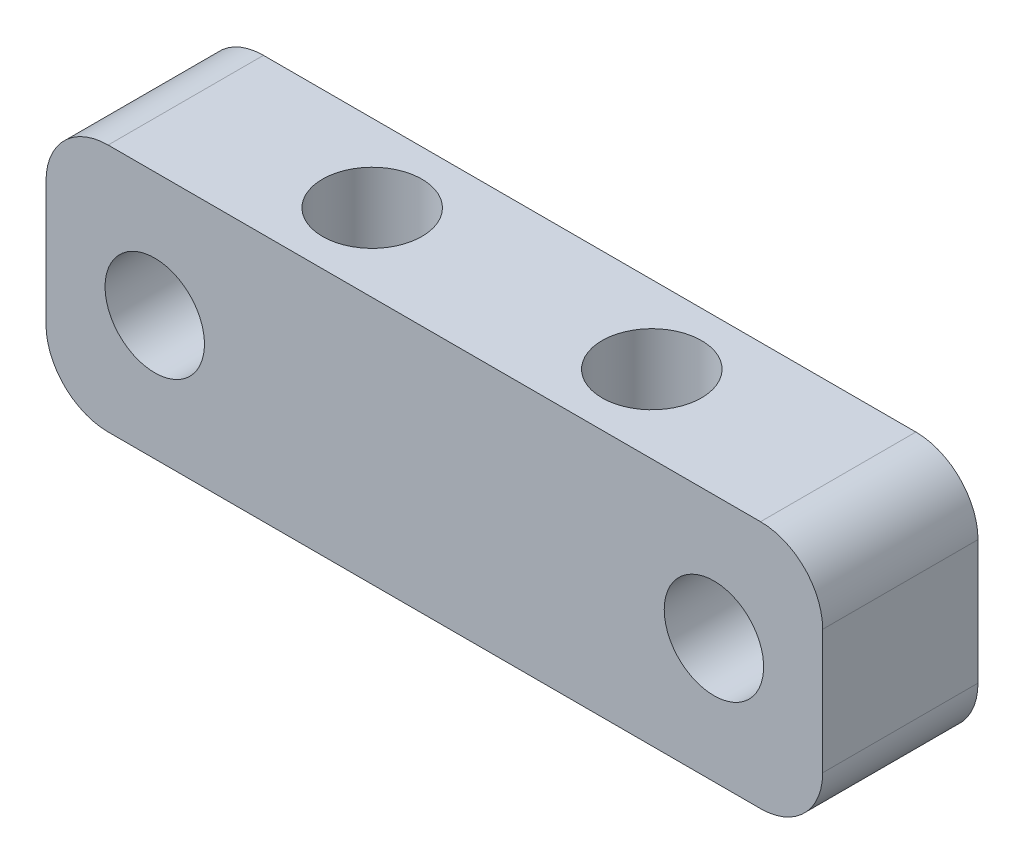
SolidWorks part; units mm, degrees
ref_plane "Front Plane" through (0, 0, 0) normal (0, 0, 1) x (1, 0, 0)
ref_plane "Top Plane" through (0, 0, 0) normal (0, 1, 0) x (1, 0, 0)
ref_plane "Right Plane" through (0, 0, 0) normal (1, 0, 0) x (0, 0, -1)
sketch "Sketch1" plane through (0, 0, 0) normal (0, 1, 0) x (1, 0, 0)
  line L1 (0, 0) -> (25, 0)
  line L2 (0, 0) -> (0, 5)
  line L3 (0, 5) -> (25, 5)
  line L4 (25, 0) -> (25, 5)
  line L5 (5, 5) -> (20, 5) construction
  line L6 (5, 5) -> (5, 0) construction
  line L7 (5, 0) -> (20, 0) construction
  line L8 (20, 5) -> (20, 0) construction
  circle A0 centre (8, 2.5) radius 1.6
  circle A1 centre (17, 2.5) radius 1.6
  point P13 (12.5, 0)
  point P14 (12.5, 0)
  point P16 (0, 2.5)
  dimension "D3" = 15
  dimension "D5" = 3
  dimension "D6" = 3.2
  dimension "D1" = 25
  dimension "D2" = 5
  dimension "D4" = 3
extrude "Boss-Extrude1" add sketch "Sketch1" along normal blind 8
sketch "Sketch2" plane through (0, 0, -5) normal (0, 0, -1) x (-1, 0, 0)
  line L0 (-25, 8) -> (0, 8) construction
  line L1 (-17.5, 8) -> (-7.5, 8) construction
  line L2 (-17.5, 8) -> (-17.5, 0) construction
  line L3 (-17.5, 0) -> (-7.5, 0) construction
  line L4 (-7.5, 8) -> (-7.5, 0) construction
  line L5 (-12.5, 8) -> (-12.5, 0) construction
  line L6 (-25, 0) -> (0, 0) construction
  line L7 (-25, 8) -> (-25, 0) construction
  line L8 (0, 8) -> (0, 0) construction
  circle A0 centre (-21.5, 4) radius 1.6
  circle A1 centre (-3.5, 4) radius 1.6
  point P16 (-25, 4)
  dimension "D2" = 3.5
  dimension "D3" = 3.5
  dimension "D4" = 3.2
  dimension "D1" = 10
extrude "Cut-Extrude1" cut sketch "Sketch2" against normal blind 8
fillet "Fillet1" radius 2 4 edges at (0, 8, -2.5) (0, 0, -2.5) (25, 0, -2.5) (25, 8, -2.5)
